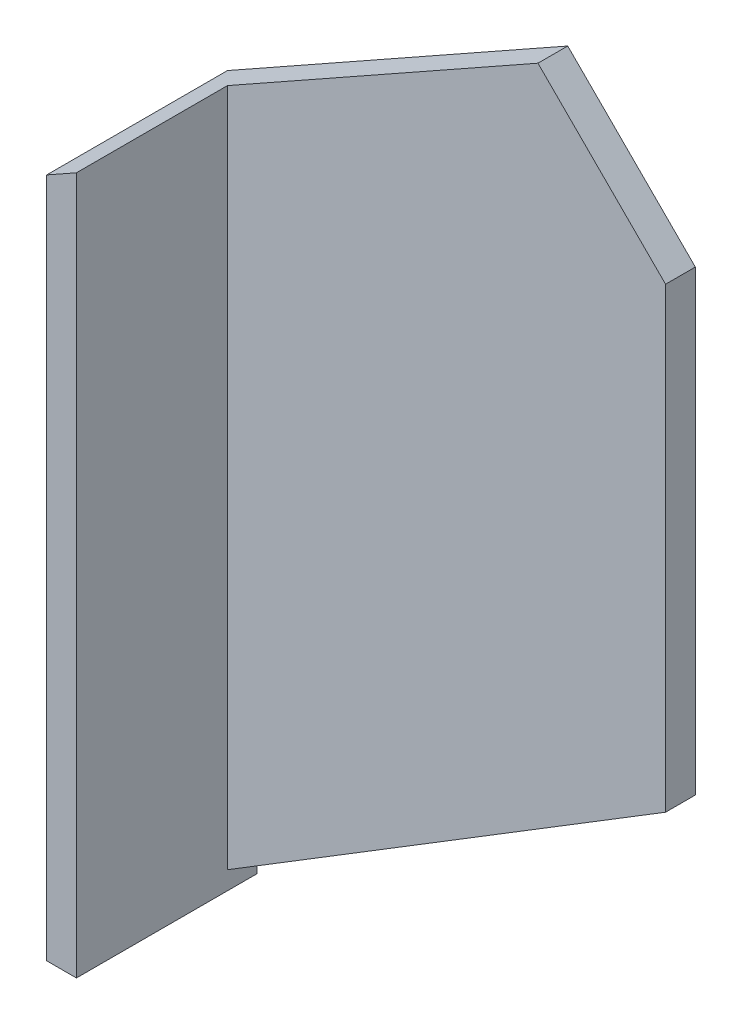
SolidWorks part; units mm, degrees
ref_plane "前视基准面" through (0, 0, 0) normal (0, 0, 1) x (1, 0, 0)
ref_plane "上视基准面" through (0, 0, 0) normal (0, 1, 0) x (1, 0, 0)
ref_plane "右视基准面" through (0, 0, 0) normal (1, 0, 0) x (0, 0, -1)
sketch "草图1" plane through (0, 0, 0) normal (0, 0, 1) x (1, 0, 0)
  line L0 (-1074.6542, -63.3767) -> (48925.3458, -63.3767) construction
  line L1 (-159.1564, -1011.9129) -> (-159.1564, 48988.0871) construction
  line L2 (-119.6564, -63.3767) -> (-119.6564, 256.6233)
  line L3 (-1159.1564, 71.6233) -> (48840.8436, 71.6233) construction
  line L4 (100.3436, 71.6233) -> (100.3436, 286.6233)
  line L5 (40.3436, -1032.1436) -> (40.3436, 48967.8564) construction
  line L6 (-1249.4209, 346.6233) -> (48750.5791, 346.6233) construction
  line L7 (-119.6564, -63.3767) -> (100.3436, 71.6233)
  line L8 (100.3436, 286.6233) -> (40.3436, 346.6233)
  line L9 (40.3436, 346.6233) -> (-119.6564, 256.6233)
  line L10 (1840.8436, -949.9726) -> (1840.8436, 49050.0274) construction
  line L11 (-67.2456, 2321.6233) -> (49932.7544, 2321.6233) construction
  line L12 (1840.8436, 2321.6233) -> (-31377.3484, -35048.8426) construction
  circle A0 centre (-16.3182, 232.3163) radius 13
  circle A1 centre (36.8309, 292.1091) radius 13
  point P21 (-159.1564, 71.6233)
  point P22 (-16.3182, 232.3163)
  point P23 (36.8309, 292.1091)
  dimension "D12" = 26
  dimension "D13" = 26
  dimension "D1" = 320
  dimension "D2" = 39.5
  dimension "D3" = 135
  dimension "D4" = 215
  dimension "D5" = 220
  dimension "D6" = 60
  dimension "D7" = 275
  dimension "D8" = 2000
  dimension "D9" = 2250
  dimension "D10" = 215
  dimension "D11" = 295
extrude "凸台-拉伸1" add sketch "草图1" along normal blind 14
sketch "草图3" plane through (0, 0, 14) normal (0, 0, 1) x (1, 0, 0)
  line L0 (-105.6564, 264.4983) -> (-105.6564, -54.7858)
  line L1 (40.3436, 346.6233) -> (-119.6564, 256.6233) construction
  line L2 (-119.6564, -63.3767) -> (100.3436, 71.6233) construction
  line L3 (-119.6564, 256.6233) -> (-119.6564, -63.3767) construction
  line L9 (-119.6564, -63.3767) -> (100.3436, 71.6233)
  line L10 (100.3436, 71.6233) -> (100.3436, 286.6233)
  line L11 (100.3436, 286.6233) -> (40.3436, 346.6233)
  line L12 (40.3436, 346.6233) -> (-119.6564, 256.6233)
  line L13 (-119.6564, 256.6233) -> (-119.6564, -63.3767)
  line L14 (-119.6564, -63.3767) -> (-105.6564, -54.7858)
  line L17 (-105.6564, 264.4983) -> (-119.6564, 256.6233)
  line L18 (-119.6564, 256.6233) -> (-119.6564, -63.3767)
  dimension "D1" = 14
  dimension "D2" = 0
extrude "凸台-拉伸2" add sketch "草图3" along normal blind 71
sketch "草图5" plane through (-119.6564, 0, 0) normal (-1, 0, 0) x (0, 0, 1)
  line L0 (47, 256.6233) -> (47, -63.3767) construction
  line L1 (85, 256.6233) -> (0, 256.6233) construction
  line L2 (85, -63.3767) -> (0, -63.3767) construction
  line L3 (85, 256.6233) -> (85, -63.3767) construction
  line L4 (0, 216.6233) -> (85, 216.6233) construction
  line L5 (0, 256.6233) -> (0, -63.3767) construction
  circle A0 centre (47, 216.6233) radius 13
  point P12 (47, 216.6233)
  dimension "D1" = 38
  dimension "D2" = 40
extrude "切除-拉伸3" cut sketch "草图5" against normal through all
pattern_linear "阵列(线性)1" count 4 spacing 80 along (0, -1, 0) of "切除-拉伸3"
sketch "草图7" plane through (-119.6564, 0, 0) normal (-1, 0, 0) x (0, 0, 1)
  line L0 (85, 256.6233) -> (85, -63.3767) construction
  line L1 (0, 256.6233) -> (85, 256.6233)
  line L2 (0, 256.6233) -> (0, -63.3767)
  line L3 (0, -63.3767) -> (85, -63.3767)
  line L4 (85, 256.6233) -> (85, -63.3767)
  line L5 (0, 256.6233) -> (0, -63.3767) construction
  line L6 (85, -63.3767) -> (0, -63.3767) construction
  line L7 (85, 256.6233) -> (0, 256.6233) construction
extrude "凸台-拉伸3" add sketch "草图7" against normal blind 14
sketch "草图8" plane through (0, 0, 14) normal (0, 0, 1) x (1, 0, 0)
  line L0 (-119.6564, 256.6233) -> (40.3436, 346.6233)
  line L1 (40.3436, 346.6233) -> (100.3436, 286.6233)
  line L2 (100.3436, 286.6233) -> (100.3436, 71.6233)
  line L3 (100.3436, 71.6233) -> (-119.6564, -63.3767)
  line L4 (-119.6564, -63.3767) -> (-119.6564, 256.6233)
  line L5 (-105.6564, -54.7858) -> (100.3436, 71.6233) construction
extrude "凸台-拉伸4" add sketch "草图8" against normal blind 14
